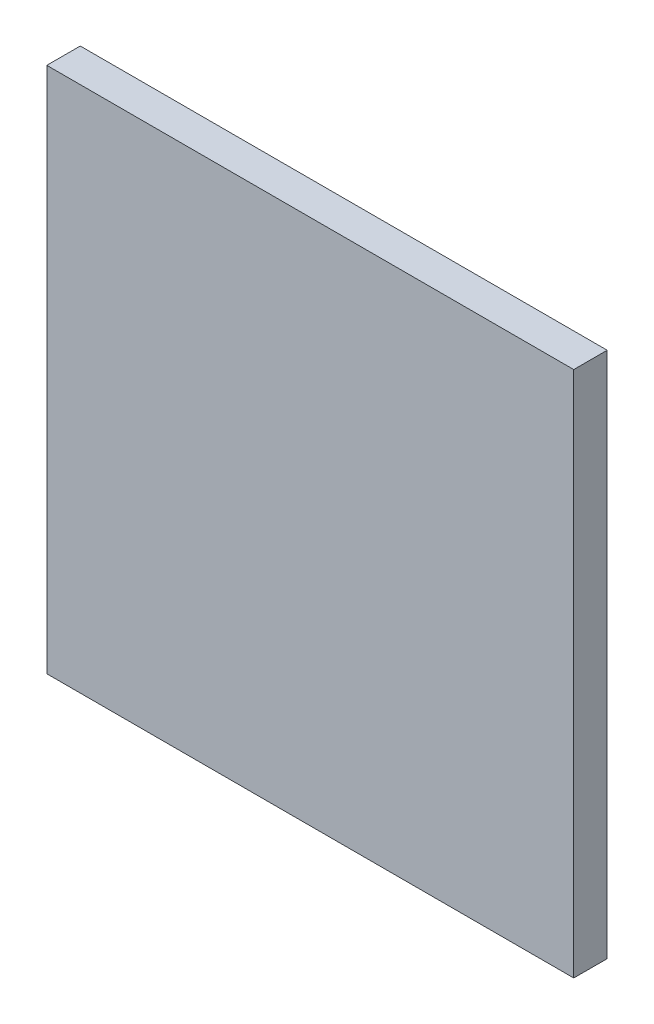
SolidWorks part; units mm, degrees
ref_plane "Front Plane" through (0, 0, 0) normal (0, 0, 1) x (1, 0, 0)
ref_plane "Top Plane" through (0, 0, 0) normal (0, 1, 0) x (1, 0, 0)
ref_plane "Right Plane" through (0, 0, 0) normal (1, 0, 0) x (0, 0, -1)
sketch "Sketch1" plane through (0, 0, 0) normal (0, 0, 1) x (1, 0, 0)
  line L1 (-43.2836, 26.1816) -> (56.7164, 26.1816)
  line L2 (-43.2836, 26.1816) -> (-43.2836, -73.8184)
  line L3 (-43.2836, -73.8184) -> (56.7164, -73.8184)
  line L4 (56.7164, 26.1816) -> (56.7164, -73.8184)
  dimension "D1" = 100
  dimension "D2" = 100
extrude "Boss-Extrude1" add sketch "Sketch1" along normal blind 6.35
